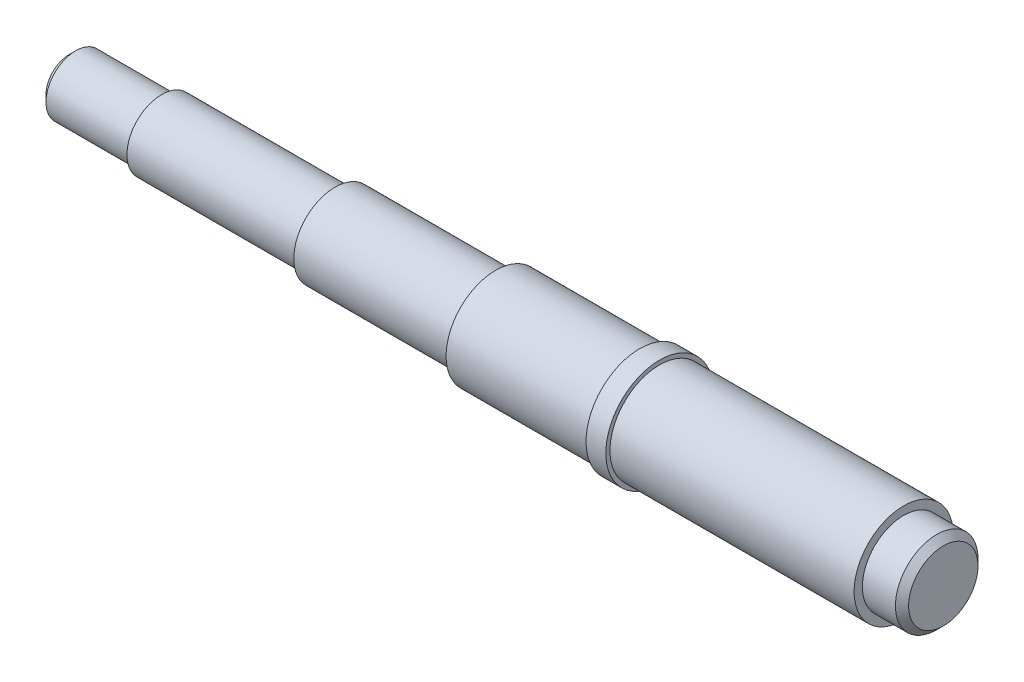
SolidWorks part; units mm, degrees
ref_plane "前视基准面" through (0, 0, 0) normal (0, 0, 1) x (1, 0, 0)
ref_plane "上视基准面" through (0, 0, 0) normal (0, 1, 0) x (1, 0, 0)
ref_plane "右视基准面" through (0, 0, 0) normal (1, 0, 0) x (0, 0, -1)
sketch "草图1" plane through (0, 0, 0) normal (0, 0, 1) x (1, 0, 0)
  line L0 (0, 0) -> (0, 9)
  line L1 (0, 9) -> (28, 9)
  line L2 (28, 9) -> (28, 10.5)
  line L3 (28, 10.5) -> (80.5, 10.5)
  line L4 (80.5, 10.5) -> (80.5, 12.5)
  line L5 (80.5, 12.5) -> (129.1, 12.5)
  line L6 (129.1, 12.5) -> (129.1, 15)
  line L7 (129.1, 15) -> (172.7, 15)
  line L8 (172.7, 15) -> (172.7, 16.25)
  line L9 (172.7, 16.25) -> (178.7, 16.25)
  line L10 (178.7, 16.25) -> (178.7, 15)
  line L11 (178.7, 15) -> (252.6, 15)
  line L12 (252.6, 15) -> (252.6, 12.5)
  line L13 (252.6, 12.5) -> (264.6, 12.5)
  line L14 (264.6, 12.5) -> (264.6, 0)
  line L15 (264.6, 0) -> (0, 0)
  dimension "D1" = 9
  dimension "D2" = 10.5
  dimension "D3" = 12.5
  dimension "D4" = 15
  dimension "D5" = 15
  dimension "D6" = 12.5
  dimension "D7" = 28
  dimension "D8" = 52.5
  dimension "D9" = 48.6
  dimension "D10" = 43.6
  dimension "D11" = 6
  dimension "D12" = 16.25
  dimension "D13" = 12
  dimension "D14" = 73.9
revolve "旋转1" add sketch "草图1" angle 360 about L15
chamfer "倒角1" distance 2 angle 45 2 edges at (264.6, 0, -12.5) (0, 0, -9)
sketch "草图2" plane through (0, 0, 0) normal (0, 0, 1) x (1, 0, 0)
  line L0 (129.1, 0) -> (172.7, 0)
  line L1 (129.1, 15) -> (129.1, -15) construction
  line L2 (172.7, 15) -> (172.7, -15) construction
  line L4 (138.4, 4) -> (163.4, 4)
  line L5 (138.4, 4) -> (138.4, -4)
  line L6 (138.4, -4) -> (163.4, -4)
  line L7 (163.4, 4) -> (163.4, -4)
  line L8 (150.9, -4) -> (150.9, 4) construction
  line L9 (138.4, 0) -> (163.4, 0) construction
  point P6 (150.9, 0)
  dimension "D1" = 8
  dimension "D2" = 25
extrude "切除-拉伸1" cut sketch "草图2" against normal blind 28 from offset 11.5 contours L7 L0 L5 L6 | L7 L4 L5 L0 offset against normal yes
sketch "草图3" plane through (264.6, 0, 0) normal (1, 0, 0) x (0, 0, -1)
  line L0 (0, 0) -> (0, 10.5)
  circle A0 centre (0, 0) radius 10.5 construction
